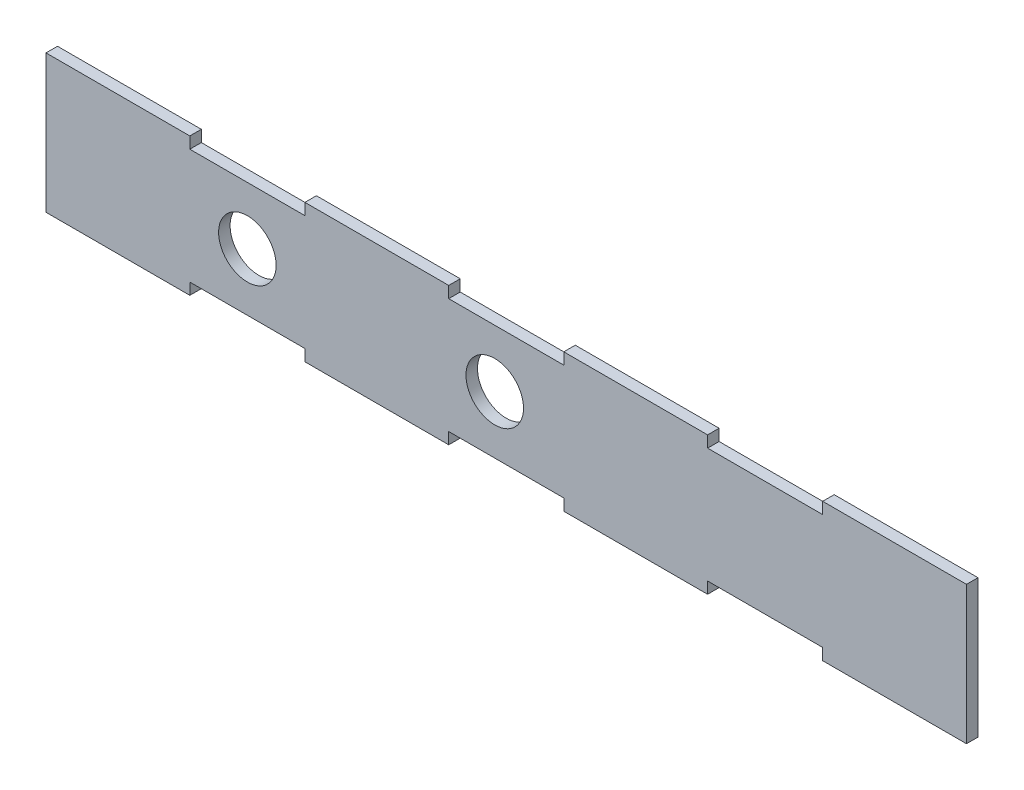
SolidWorks part; units mm, degrees
ref_plane "Спереди" through (0, 0, 0) normal (0, 0, 1) x (1, 0, 0)
ref_plane "Сверху" through (0, 0, 0) normal (0, 1, 0) x (1, 0, 0)
ref_plane "Справа" through (0, 0, 0) normal (1, 0, 0) x (0, 0, -1)
sketch "Эскиз1" plane through (0, 0, 0) normal (0, 0, 1) x (1, 0, 0)
  line L0 (135, 0) -> (160, 0)
  line L1 (0, 0) -> (25, 0)
  line L2 (0, 0) -> (0, 24)
  line L3 (21.9832, 24) -> (25, 24)
  line L4 (160, 0) -> (160, 24)
  line L5 (0, 24) -> (25, 24)
  line L6 (0, 24) -> (0, 22)
  line L8 (25, 24) -> (25, 22)
  line L9 (45, 24) -> (70, 24)
  line L10 (45, 24) -> (45, 22)
  line L12 (70, 24) -> (70, 22)
  line L13 (90, 24) -> (115, 24)
  line L14 (90, 24) -> (90, 22)
  line L16 (115, 24) -> (115, 22)
  line L17 (0, 0) -> (25, 0)
  line L18 (0, 0) -> (0, 2)
  line L20 (25, 0) -> (25, 2)
  line L21 (45, 0) -> (70, 0)
  line L22 (45, 0) -> (45, 2)
  line L24 (70, 0) -> (70, 2)
  line L26 (90, 0) -> (90, 2)
  line L28 (115, 0) -> (115, 2)
  line L29 (160, 24) -> (135, 24)
  line L30 (160, 24) -> (160, 22)
  line L32 (135, 24) -> (135, 22)
  line L33 (160, 0) -> (135, 0)
  line L34 (160, 0) -> (160, 2)
  line L36 (135, 0) -> (135, 2)
  line L37 (115, 0) -> (90, 0)
  line L38 (25, 22) -> (45, 22)
  line L39 (70, 22) -> (90, 22)
  line L40 (115, 22) -> (135, 22)
  line L41 (25, 2) -> (45, 2)
  line L42 (70, 2) -> (90, 2)
  line L43 (115, 2) -> (135, 2)
  line L44 (90, 24) -> (160, 24)
  line L45 (25.3892, 22) -> (45, 22)
  line L46 (45, 24) -> (70, 24)
  line L47 (45, 0) -> (70, 0)
  circle A2 centre (78, 12) radius 5
  circle A3 centre (35, 12) radius 5
  dimension "D31" = 10
  dimension "D34" = 10
  dimension "D1" = 24
  dimension "D2" = 160
  dimension "D3" = 2
  dimension "D4" = 2
  dimension "D5" = 2
  dimension "D6" = 2
  dimension "D7" = 2
  dimension "D8" = 2
  dimension "D9" = 25
  dimension "D10" = 25
  dimension "D11" = 25
  dimension "D12" = 25
  dimension "D13" = 25
  dimension "D14" = 25
  dimension "D15" = 20
  dimension "D16" = 20
  dimension "D17" = 20
  dimension "D18" = 20
  dimension "D19" = 20
  dimension "D20" = 20
  dimension "D21" = 2
  dimension "D22" = 2
  dimension "D32" = 12
  dimension "D33" = 82
  dimension "D35" = 12
  dimension "D36" = 125
extrude "Бобышка-Вытянуть1" add sketch "Эскиз1" along normal blind 2
